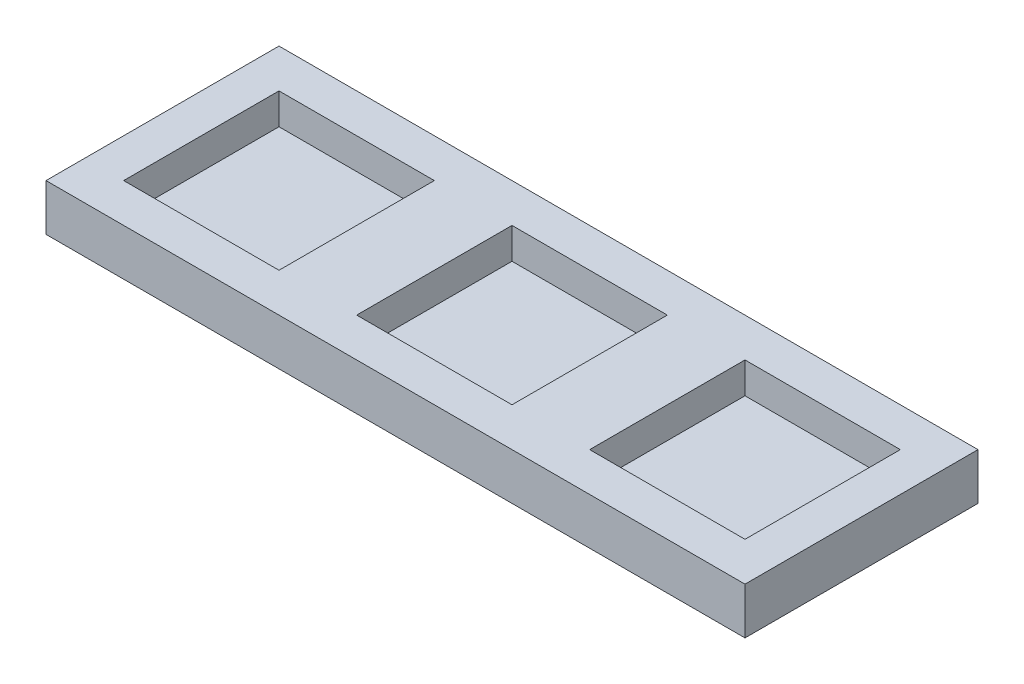
SolidWorks part; units mm, degrees
ref_plane "前视基准面" through (0, 0, 0) normal (0, 0, 1) x (1, 0, 0)
ref_plane "上视基准面" through (0, 0, 0) normal (0, 1, 0) x (1, 0, 0)
ref_plane "右视基准面" through (0, 0, 0) normal (1, 0, 0) x (0, 0, -1)
sketch "草图1" plane through (0, 0, 0) normal (0, 1, 0) x (1, 0, 0)
  line L0 (225, 0) -> (-225, 0)
  line L1 (-225, 0) -> (-225, -150)
  line L2 (-225, -150) -> (225, -150)
  line L3 (225, -150) -> (225, 0)
  point P4 (0, 0)
  dimension "D1" = 450
  dimension "D2" = 150
extrude "凸台-拉伸1" add sketch "草图1" along normal blind 30
sketch "草图2" plane through (0, 30, 0) normal (0, 1, 0) x (1, 0, 0)
  line L0 (-75, 0) -> (-75, -150) construction
  line L1 (75, 0) -> (75, -150) construction
  line L2 (225, 0) -> (225, -150) construction
  line L3 (375, 0) -> (375, -150) construction
  line L4 (-225, -150) -> (225, -150)
  line L5 (225, -150) -> (225, 0)
  line L6 (225, 0) -> (-225, 0)
  line L7 (-225, 0) -> (-225, -150)
  line L8 (-225, -150) -> (225, -150) construction
  line L9 (225, -150) -> (225, 0) construction
  line L10 (225, 0) -> (-225, 0) construction
  line L11 (-225, 0) -> (-225, -150) construction
  line L12 (-225, 0) -> (-75, -150) construction
  line L13 (-225, -150) -> (-75, 0) construction
  line L14 (-50, -25) -> (50, -25)
  line L15 (-200, -25) -> (-100, -25)
  line L16 (-200, -25) -> (-200, -125)
  line L17 (-200, -125) -> (-100, -125)
  line L18 (-100, -25) -> (-100, -125)
  line L19 (-150, -125) -> (-150, -25) construction
  line L20 (-200, -75) -> (-100, -75) construction
  line L21 (-50, -25) -> (-50, -125)
  line L22 (-50, -125) -> (50, -125)
  line L23 (50, -25) -> (50, -125)
  line L24 (100, -25) -> (200, -25)
  line L25 (100, -25) -> (100, -125)
  line L26 (100, -125) -> (200, -125)
  line L27 (200, -25) -> (200, -125)
  line L28 (250, -25) -> (350, -25)
  line L29 (250, -25) -> (250, -125)
  line L30 (250, -125) -> (350, -125)
  line L31 (350, -25) -> (350, -125)
  line L32 (400, -25) -> (500, -25)
  line L33 (400, -25) -> (400, -125)
  line L34 (400, -125) -> (500, -125)
  line L35 (500, -25) -> (500, -125)
  point P2 (-150, -75)
  dimension "D3" = 150
  dimension "D4" = 100
  dimension "D5" = 5
  dimension "D6" = 150
  dimension "D1" = 0
  dimension "D2" = 5
extrude "切除-拉伸1" cut sketch "草图2" against normal blind 20
sketch "草图3" plane through (0, 0, 0) normal (0, -1, 0) x (1, 0, 0)
  line L0 (-225, 150) -> (225, 150) construction
  line L1 (-225, 150) -> (225, 150) construction
  line L2 (0, 150) -> (0, -200) construction
  dimension "D1" = 350
